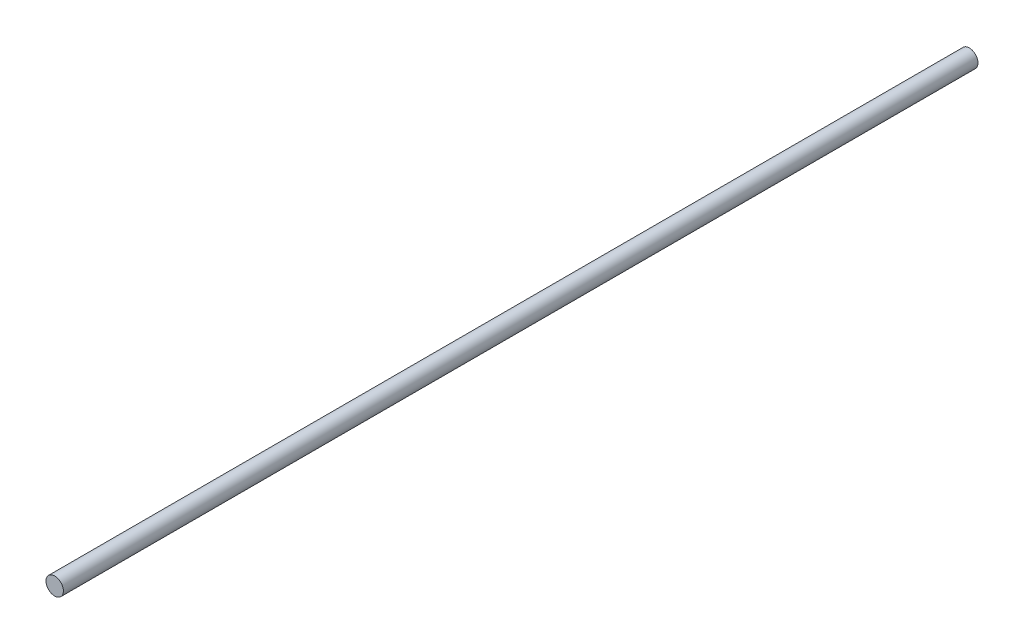
SolidWorks part; units mm, degrees
ref_plane "Front Plane" through (0, 0, 0) normal (0, 0, 1) x (1, 0, 0)
ref_plane "Top Plane" through (0, 0, 0) normal (0, 1, 0) x (1, 0, 0)
ref_plane "Right Plane" through (0, 0, 0) normal (1, 0, 0) x (0, 0, -1)
sketch "Sketch1" plane through (0, 0, 0) normal (0, 0, 1) x (1, 0, 0)
  circle A1 centre (20, 0) radius 1
extrude "Boss-Extrude1" add sketch "Sketch1" against normal blind 105
